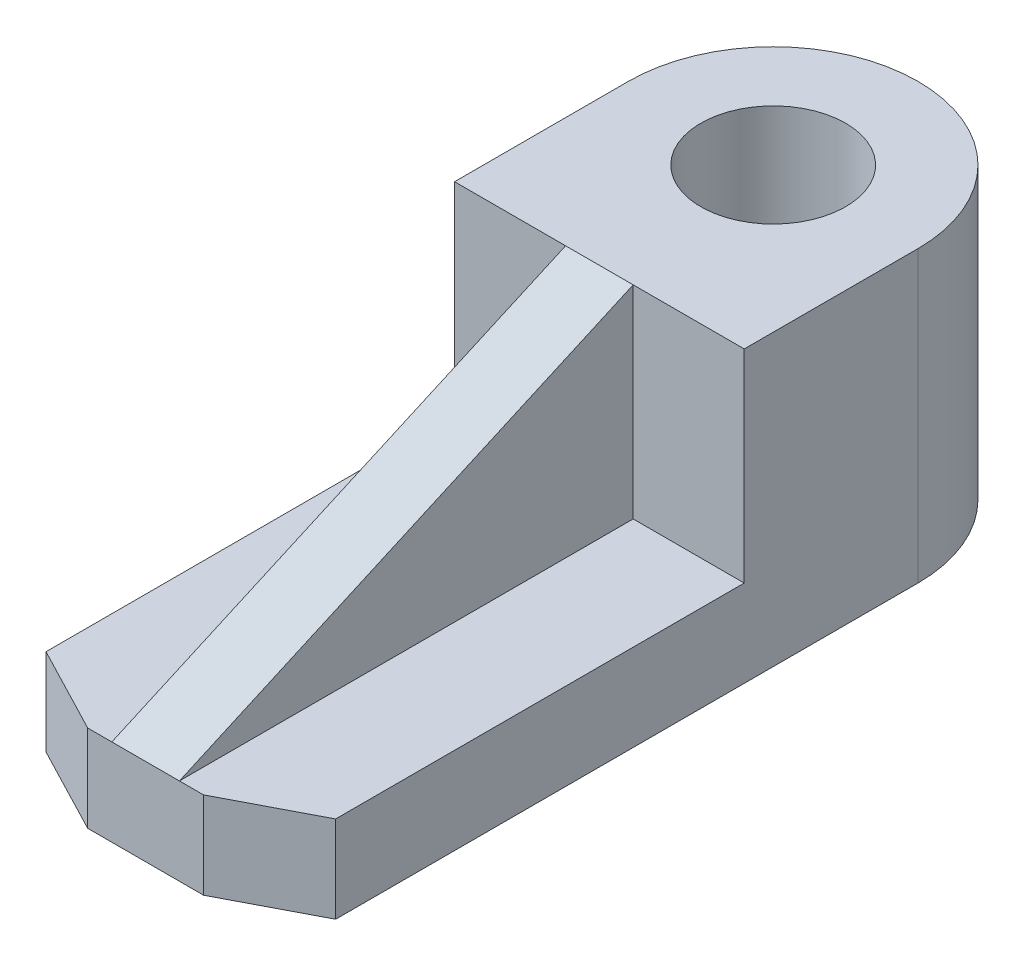
SolidWorks part; units mm, degrees
ref_plane "Front Plane" through (0, 0, 0) normal (0, 0, 1) x (1, 0, 0)
ref_plane "Top Plane" through (0, 0, 0) normal (0, 1, 0) x (1, 0, 0)
ref_plane "Right Plane" through (0, 0, 0) normal (1, 0, 0) x (0, 0, -1)
sketch "Sketch1" plane through (0, 0, 0) normal (0, 1, 0) x (1, 0, 0)
  line L0 (-5.0072, 0) -> (6.9928, 0)
  line L1 (6.9928, 0) -> (15.9928, 4.6835)
  line L2 (15.9928, 4.6835) -> (15.9928, 65)
  line L3 (-5.0072, 0) -> (-14.0072, 4.6835)
  line L4 (-14.0072, 4.6835) -> (-14.0072, 65)
  arc A0 (-14.0072, 65) -> (15.9928, 65) centre (0.9928, 65) cw
  dimension "D1" = 12
  dimension "D2" = 9
  dimension "D3" = 9
  dimension "D4" = 65
extrude "Boss-Extrude1" add sketch "Sketch1" along normal blind 9
sketch "Sketch2" plane through (0, 9, 0) normal (0, 1, 0) x (1, 0, 0)
  line L0 (-14.0072, 65) -> (15.9928, 65)
  line L1 (15.9928, 4.6835) -> (15.9928, 65) construction
  line L2 (-14.0072, 65) -> (-14.0072, 47)
  line L3 (-14.0072, 65) -> (-14.0072, 4.6835) construction
  line L4 (-14.0072, 47) -> (15.9928, 47)
  line L5 (15.9928, 47) -> (15.9928, 65)
  line L6 (-14.0072, 65) -> (-14.0072, 47)
  line L7 (15.9928, 47) -> (15.9928, 65)
  arc A0 (15.9928, 65) -> (-14.0072, 65) centre (0.9928, 65) ccw construction
  arc A1 (-14.0072, 65) -> (15.9928, 65) centre (0.9928, 65) cw
  circle A2 centre (0.9928, 65) radius 7.5
  line M5 (15.9928, 4.6835) -> (15.9928, 65)
  arc M6 (15.9928, 65) -> (-14.0072, 65) centre (0.9928, 65) ccw
  line M7 (-14.0072, 65) -> (-14.0072, 4.6835)
  dimension "D1" = 18
extrude "Boss-Extrude2" add sketch "Sketch2" along normal blind 21 contours A2 L0 L4 M7 M5 | A2 L0 M6
ref_plane "Plane1" through (0.9928, 0, 0) normal (1, 0, 0) x (0, 0, -1)
sketch "Sketch3" plane through (0.9928, 0, 0) normal (1, 0, 0) x (0, 0, -1)
  line L0 (0, 9) -> (47, 30)
  line L2 (47, 30) -> (47, 9)
  line L3 (47, 9) -> (0, 9)
extrude "Boss-Extrude3" add sketch "Sketch3" along normal mid plane 7
sketch "Sketch4" plane through (0, 9, 0) normal (0, 1, 0) x (1, 0, 0)
  circle A0 centre (0.9928, 65) radius 7.5
extrude "Cut-Extrude1" cut sketch "Sketch4" against normal through all
